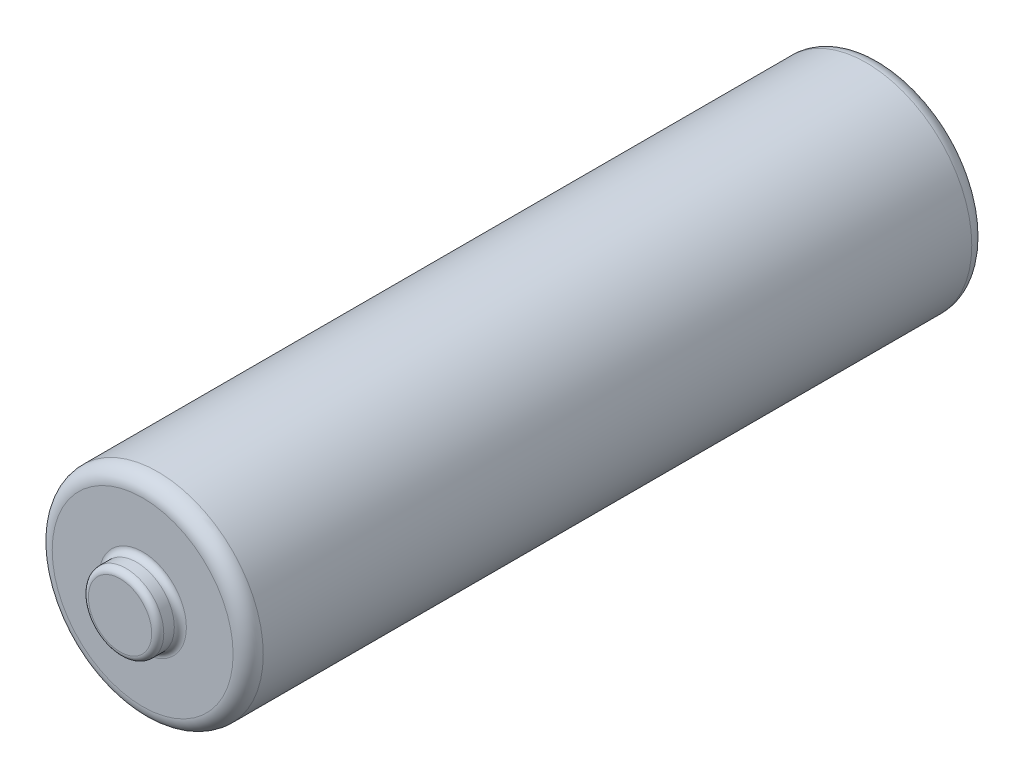
SolidWorks part; units mm, degrees
ref_plane "Front Plane" through (0, 0, 0) normal (0, 0, 1) x (1, 0, 0)
ref_plane "Top Plane" through (0, 0, 0) normal (0, 1, 0) x (1, 0, 0)
ref_plane "Right Plane" through (0, 0, 0) normal (1, 0, 0) x (0, 0, -1)
sketch "Sketch1" plane through (0, 0, 0) normal (0, 0, 1) x (1, 0, 0)
  circle A0 centre (0, 0) radius 7
  dimension "D1" = 14
extrude "Boss-Extrude1" add sketch "Sketch1" along normal blind 49
sketch "Sketch2" plane through (0, 0, 49) normal (0, 0, 1) x (1, 0, 0)
  circle A0 centre (0, 0) radius 2.5
  dimension "D1" = 5
extrude "Boss-Extrude2" add sketch "Sketch2" along normal blind 1.5
fillet "Fillet1" radius 1 2 edges at (7, 0, 0) (7, 0, 49)
fillet "Fillet2" radius 0.4 2 edges at (2.5, 0, 50.5) (2.5, 0, 49)
